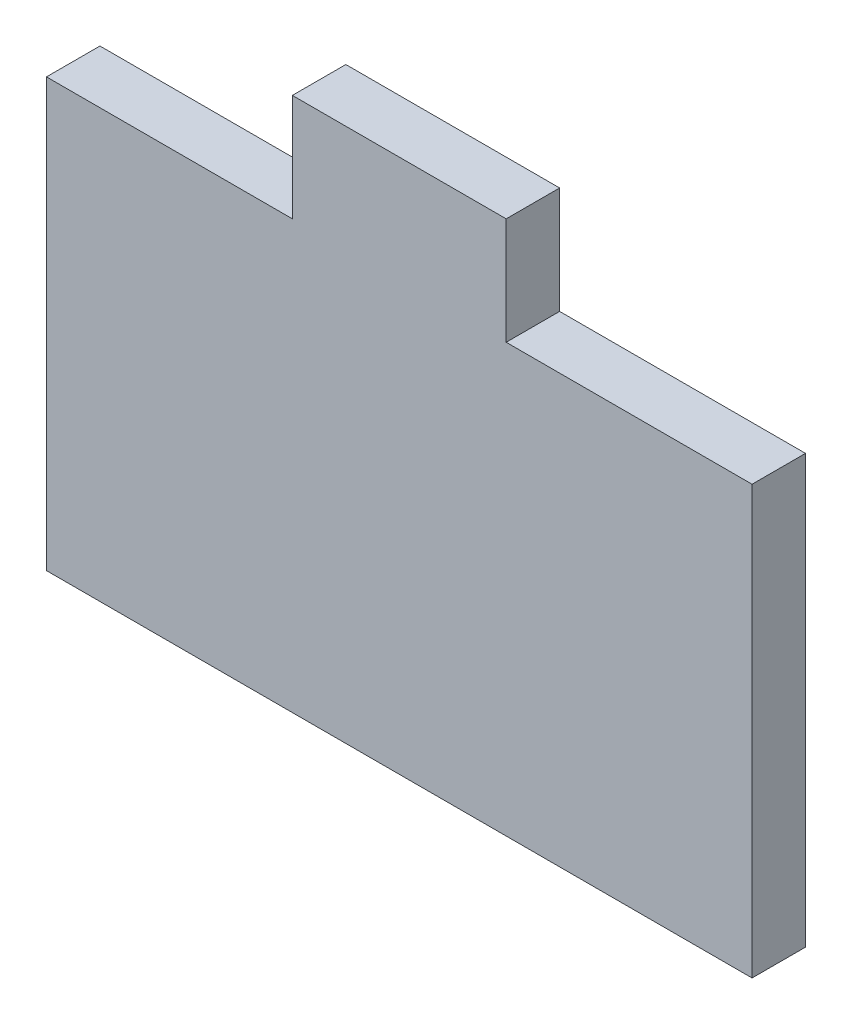
SolidWorks part; units mm, degrees
ref_plane "Front Plane" through (0, 0, 0) normal (0, 0, 1) x (1, 0, 0)
ref_plane "Top Plane" through (0, 0, 0) normal (0, 1, 0) x (1, 0, 0)
ref_plane "Right Plane" through (0, 0, 0) normal (1, 0, 0) x (0, 0, -1)
sketch "Sketch1" plane through (0, 0, 0) normal (0, 0, 1) x (1, 0, 0)
  line L1 (16.5, 10) -> (-16.5, 10)
  line L2 (16.5, 10) -> (16.5, -10)
  line L3 (16.5, -10) -> (-16.5, -10)
  line L4 (-16.5, 10) -> (-16.5, -10)
  line L5 (16.5, 10) -> (-16.5, -10) construction
  line L6 (16.5, -10) -> (-16.5, 10) construction
  line L7 (5, 15) -> (-5, 15)
  line L8 (5, 15) -> (5, 10)
  line L9 (5, 10) -> (-5, 10)
  line L10 (-5, 15) -> (-5, 10)
  point P0 (0, 0)
  point P10 (0, 10)
  point P11 (0, 10)
  dimension "D1" = 10
  dimension "D2" = 5
  dimension "D3" = 20
  dimension "D4" = 33
extrude "Boss-Extrude1" add sketch "Sketch1" along normal blind 2.5 contours L7 L10 L1 L8 | L1 L4 L3 L2
equation "\"thick5mm\" = 0.5"
equation "\"D1@Boss-Extrude1\"= \"thick2.5mm\""
equation "\"D2@Sketch1\" = \"thick5mm\""
equation "\"thick2.5mm\"= 0.25"
